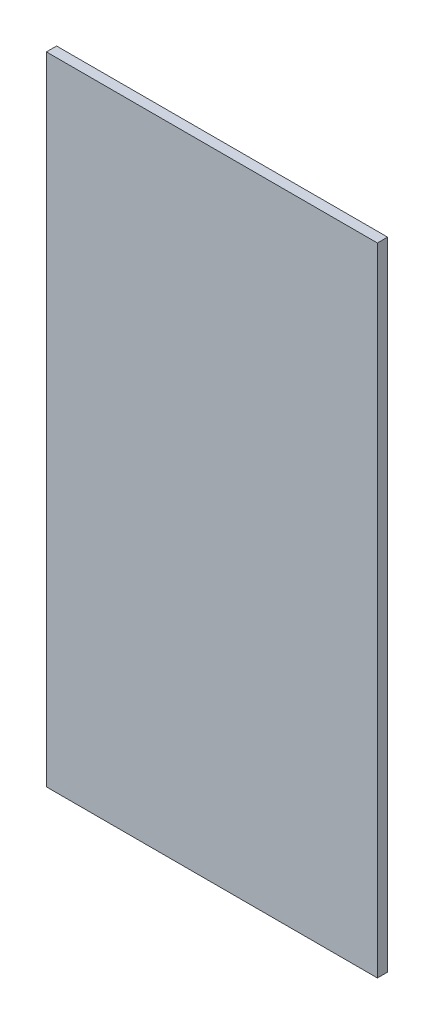
SolidWorks part; units mm, degrees
material "A-Glass Fiber"
ref_plane "Front Plane" through (0, 0, 0) normal (0, 0, 1) x (1, 0, 0)
ref_plane "Top Plane" through (0, 0, 0) normal (0, 1, 0) x (1, 0, 0)
ref_plane "Right Plane" through (0, 0, 0) normal (1, 0, 0) x (0, 0, -1)
sketch "Sketch1" plane through (0, 0, 0) normal (0, 0, 1) x (1, 0, 0)
  line L1 (0, 0) -> (52, 0)
  line L2 (0, 0) -> (0, 100)
  line L3 (0, 100) -> (52, 100)
  line L4 (52, 0) -> (52, 100)
  dimension "D1" = 100
  dimension "D2" = 52
extrude "Boss-Extrude1" add sketch "Sketch1" along normal blind 1.6
